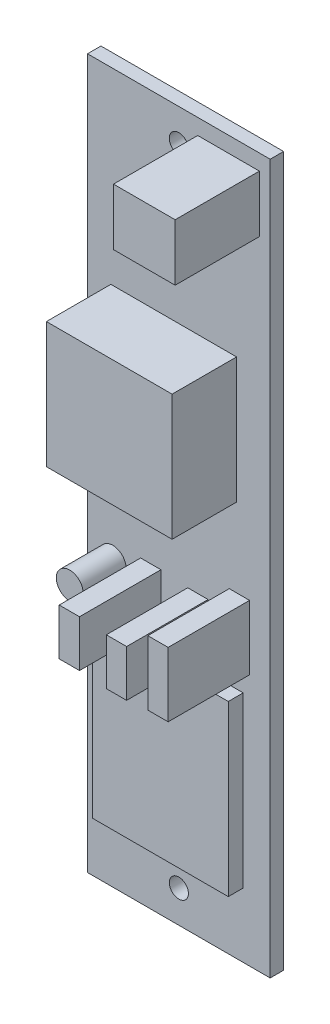
SolidWorks part; units mm, degrees
ref_plane "Front Plane" through (0, 0, 0) normal (0, 0, 1) x (1, 0, 0)
ref_plane "Top Plane" through (0, 0, 0) normal (0, 1, 0) x (1, 0, 0)
ref_plane "Right Plane" through (0, 0, 0) normal (1, 0, 0) x (0, 0, -1)
ref_plane "Plane1" through (0, 0, 1.5875) normal (0, 0, 1) x (1, 0, 0)
sketch "Sketch1" plane through (0, 0, 1.5875) normal (0, 0, 1) x (1, 0, 0)
  line L0 (10.795, -41.91) -> (10.795, 41.91)
  line L1 (10.795, 41.91) -> (-10.795, 41.91)
  line L2 (-10.795, 41.91) -> (-10.795, -41.91)
  line L3 (-10.795, -41.91) -> (10.795, -41.91)
extrude "Boss-Extrude1" add sketch "Sketch1" against normal blind 1.5875
sketch "Sketch2" plane through (0, 0, 1.5875) normal (0, 0, 1) x (1, 0, 0)
  line L0 (9.5205, 40.0554) -> (9.5205, 33.3498)
  line L1 (9.5205, 33.3498) -> (2.2307, 33.3498)
  line L2 (2.2307, 33.3498) -> (2.2307, 40.0554)
  line L3 (2.2307, 40.0554) -> (9.5205, 40.0554)
extrude "Boss-Extrude2" add sketch "Sketch2" along normal blind 9.9568
sketch "Sketch3" plane through (0, 0, 1.5875) normal (0, 0, 1) x (1, 0, 0)
  line L0 (-8.0349, 19.685) -> (6.8241, 19.685)
  line L1 (6.8241, 19.685) -> (6.8241, 4.826)
  line L2 (6.8241, 4.826) -> (-8.0349, 4.826)
  line L3 (-8.0349, 4.826) -> (-8.0349, 19.685)
extrude "Boss-Extrude3" add sketch "Sketch3" along normal blind 7.62
sketch "Sketch4" plane through (0, 0, 1.5875) normal (0, 0, 1) x (1, 0, 0)
  line L0 (7.6093, -14.3129) -> (7.6093, -34.29)
  line L1 (7.6093, -34.29) -> (-8.4435, -34.29)
  line L2 (-8.4435, -34.29) -> (-8.4435, -14.3129)
  line L3 (-8.4435, -14.3129) -> (7.6093, -14.3129)
extrude "Boss-Extrude4" add sketch "Sketch4" along normal blind 1.7653
sketch "Sketch5" plane through (0, 0, 1.5875) normal (0, 0, 1) x (1, 0, 0)
  line L0 (8.3601, -4.4704) -> (8.3601, -12.0904)
  line L1 (8.3601, -12.0904) -> (5.9598, -12.0904)
  line L2 (5.9598, -12.0904) -> (5.9598, -4.4704)
  line L3 (5.9598, -4.4704) -> (8.3601, -4.4704)
extrude "Boss-Extrude5" add sketch "Sketch5" along normal blind 9.6266
sketch "Sketch6" plane through (0, 0, 1.5875) normal (0, 0, 1) x (1, 0, 0)
  line L0 (3.4539, -6.8336) -> (3.4539, -12.3454)
  line L1 (3.4539, -12.3454) -> (1.0536, -12.3454)
  line L2 (1.0536, -12.3454) -> (1.0536, -6.8336)
  line L3 (1.0536, -6.8336) -> (3.4539, -6.8336)
extrude "Boss-Extrude6" add sketch "Sketch6" along normal blind 9.6266
sketch "Sketch7" plane through (0, 0, 1.5875) normal (0, 0, 1) x (1, 0, 0)
  line L0 (-2.1162, -6.5703) -> (-2.1162, -12.0821)
  line L1 (-2.1162, -12.0821) -> (-4.5165, -12.0821)
  line L2 (-4.5165, -12.0821) -> (-4.5165, -6.5703)
  line L3 (-4.5165, -6.5703) -> (-2.1162, -6.5703)
extrude "Boss-Extrude7" add sketch "Sketch7" along normal blind 9.6266
ref_plane "Plane2" through (0, -8.5001, 0) normal (0, -1, 0) x (1, 0, 0)
sketch "Sketch8" plane through (0, -8.5001, 0) normal (0, -1, 0) x (1, 0, 0)
  line L0 (-6.2288, 6.6675) -> (-7.8163, 6.6675)
  line L1 (-7.8163, 6.6675) -> (-7.8163, 1.5875)
  line L2 (-7.8163, 1.5875) -> (-6.2288, 1.5875)
  line L3 (-6.2288, 1.5875) -> (-6.2288, 6.6675)
  line L4 (-7.8163, 6.6675) -> (-7.8163, 1.5875) construction
revolve "Revolve1" add sketch "Sketch8" angle 360 about L4
hole_wizard "M2 Clearance Hole1" positions "Sketch10" profile "Sketch9" hole size "M2" standard "ANSI Metric"
sketch "Sketch10" plane through (0, 0, 0) normal (0, 0, -1) x (-1, 0, 0)
  point P0 (0, -38.1)
  point P1 (0, 38.1)
sketch "Sketch9" plane through (0, -38.1, 0) normal (1, 0, 0) x (0, 1, 0)
  line L0 (0, 0) -> (0, 11.5443)
  line L1 (0, 11.5443) -> (1.1303, 11.5443)
  line L2 (1.1303, 11.5443) -> (1.1303, 0)
  line L5 (1.1303, 0) -> (0, 0)
  line L11 (0, -6.35) -> (0, 107.95) construction
  dimension "Thru Hole Dia." = 2.2606
  dimension "Thru Hole Depth" = 11.5443
